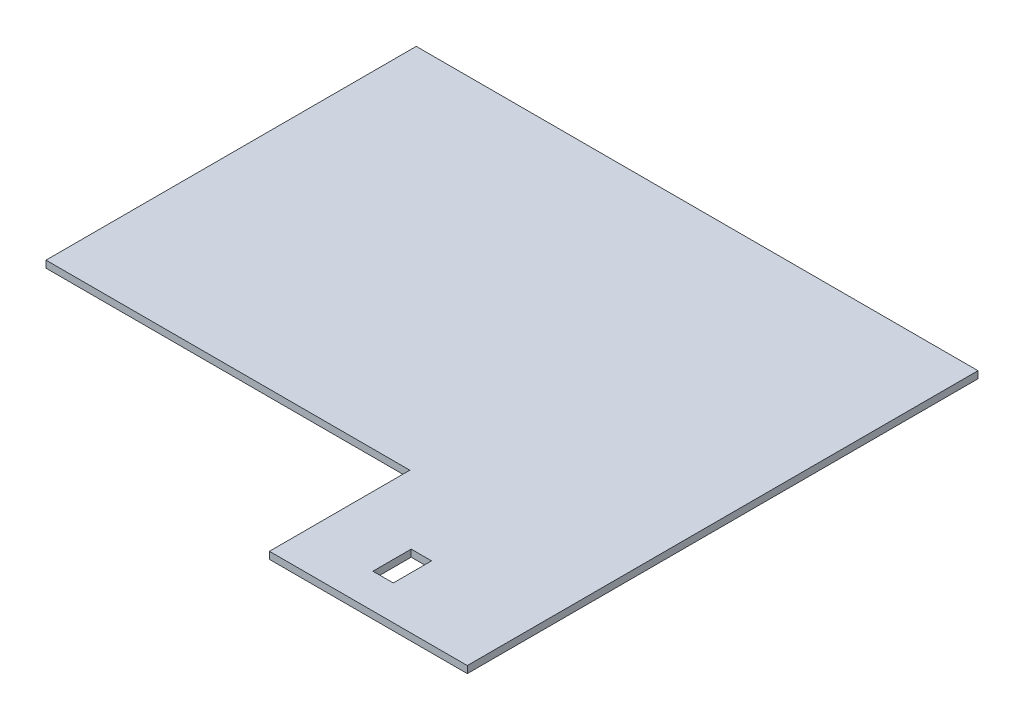
SolidWorks part; units mm, degrees
ref_plane "Alzado" through (0, 0, 0) normal (0, 0, 1) x (1, 0, 0)
ref_plane "Planta" through (0, 0, 0) normal (0, 1, 0) x (1, 0, 0)
ref_plane "Vista lateral" through (0, 0, 0) normal (1, 0, 0) x (0, 0, -1)
sketch "Croquis1" plane through (0, 0, 0) normal (0, 1, 0) x (-1, 0, 0)
  line L19 (-143.5867, 402.2958) -> (-228.5867, 402.2958)
  line L21 (-143.5867, 345.2958) -> (-143.5867, 375.2958)
  line L22 (-228.5867, 2.2958) -> (-228.5867, 402.2958)
  line L24 (211.4133, 2.2958) -> (211.4133, 292.2958)
  line L26 (-228.5867, 2.2958) -> (211.4133, 2.2958)
  line L27 (211.4133, 292.2958) -> (-73.5867, 292.2958)
  line L28 (-143.5867, 402.2958) -> (-73.5867, 402.2958)
  line L29 (-143.5867, 375.2958) -> (-143.5867, 345.2958)
  line L31 (-73.5867, 402.2958) -> (-73.5867, 292.2958)
  line L32 (-143.5867, 375.2958) -> (-127.6253, 375.2958)
  line L33 (-127.6253, 375.2958) -> (-127.6253, 345.2958)
  line L34 (-127.6253, 345.2958) -> (-143.5867, 345.2958)
  line L35 (-143.5867, 375.2958) -> (-143.5867, 345.2958)
  dimension "D1" = 400
  dimension "D2" = 440
  dimension "D3" = 85
  dimension "D4" = 290
  dimension "D5" = 70
  dimension "D7" = 30
  dimension "D8" = 27
extrude "Saliente-Extruir1" add sketch "Croquis1" along normal blind 5.5 contours L31 L28 L19 L22 L26 L24 L27 L33 L34 L21 L32
